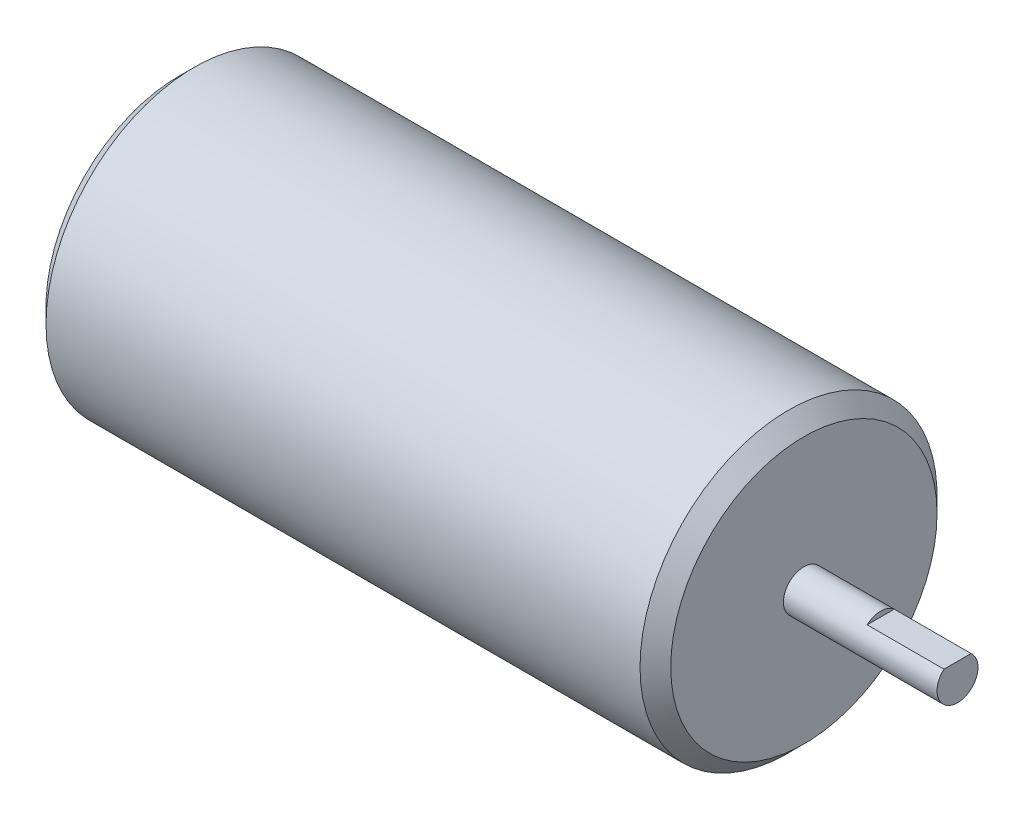
SolidWorks part; units mm, degrees
ref_plane "Спереди" through (0, 0, 0) normal (0, 0, 1) x (1, 0, 0)
ref_plane "Сверху" through (0, 0, 0) normal (0, 1, 0) x (1, 0, 0)
ref_plane "Справа" through (0, 0, 0) normal (1, 0, 0) x (0, 0, -1)
sketch "Эскиз1" plane through (0, 0, 0) normal (1, 0, 0) x (0, 0, -1)
  circle A0 centre (0, 0) radius 29
extrude "Бобышка-Вытянуть1" add sketch "Эскиз1" along normal blind 122
chamfer "Фаска1" distance 3 angle 45 2 edges at (122, 0, -29) (0, 0, -29)
sketch "Эскиз2" plane through (122, 0, 0) normal (1, 0, 0) x (0, 0, -1)
  circle A0 centre (0, 0) radius 4
extrude "Бобышка-Вытянуть2" add sketch "Эскиз2" along normal blind 30
sketch "Эскиз3" plane through (152, 0, 0) normal (1, 0, 0) x (0, 0, -1)
  line L0 (-2.6458, 3) -> (2.6458, 3)
  circle A1 centre (0, 0) radius 4 construction
  arc A2 (2.6458, 3) -> (-2.6458, 3) centre (0, 0) ccw
  dimension "D1" = 3
extrude "Вырез-Вытянуть1" cut sketch "Эскиз3" against normal blind 15
